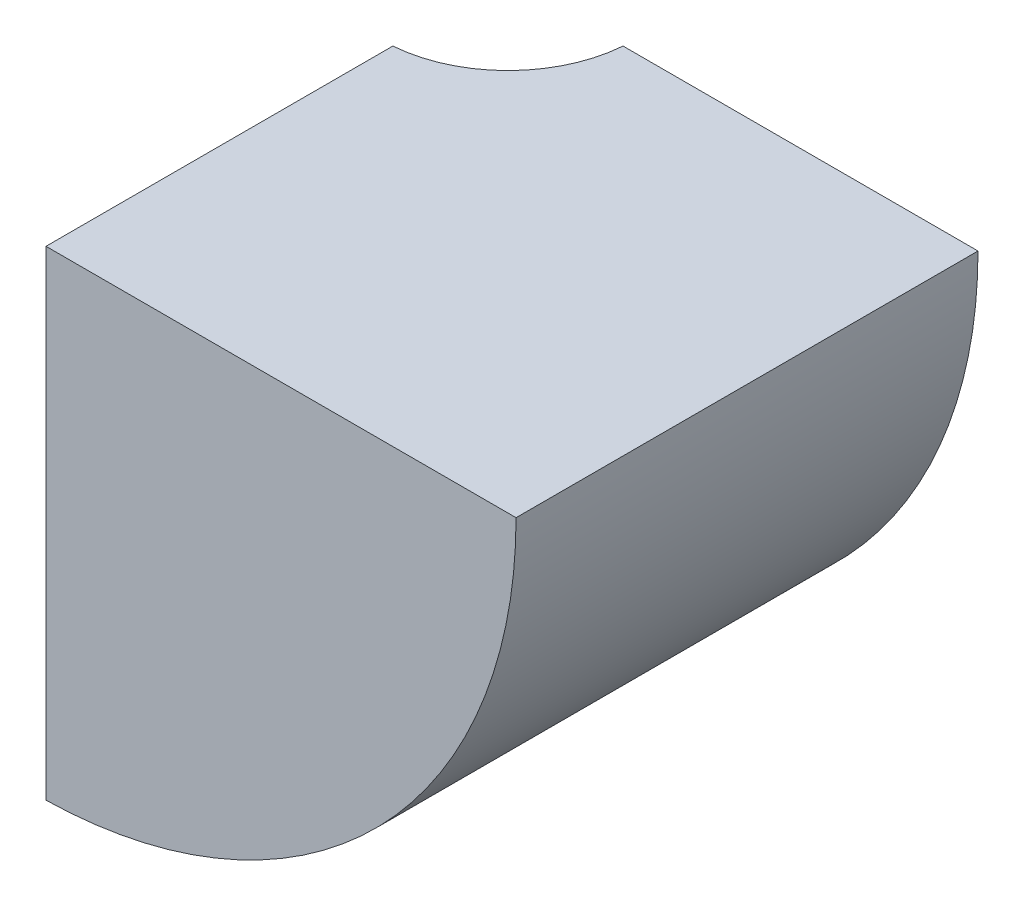
SolidWorks part; units mm, degrees
ref_plane "Front Plane" through (0, 0, 0) normal (0, 0, 1) x (1, 0, 0)
ref_plane "Top Plane" through (0, 0, 0) normal (0, 1, 0) x (1, 0, 0)
ref_plane "Right Plane" through (0, 0, 0) normal (1, 0, 0) x (0, 0, -1)
sketch "Sketch1" plane through (0, 0, 0) normal (0, 0, 1) x (1, 0, 0)
  circle A0 centre (0, 0) radius 29.5
  dimension "D1" = 59
extrude "Boss-Extrude1" add sketch "Sketch1" along normal blind 29
sketch "Sketch2" plane through (0, 0, 29) normal (0, 0, 1) x (1, 0, 0)
  line L0 (0, 0) -> (29.5, 0)
  line L1 (0, 0) -> (0, -29.5)
  circle A0 centre (0, 0) radius 29.5 construction
  arc A1 (29.5, 0) -> (0, -29.5) centre (0, 0) ccw
extrude "Cut-Extrude1" cut sketch "Sketch2" against normal through all
sketch "Sketch3" plane through (0, 0, 0) normal (0, 1, 0) x (1, 0, 0)
  circle A0 centre (0, 0) radius 7.7
  dimension "D1" = 15.4
extrude "Cut-Extrude2" cut sketch "Sketch3" against normal through all
sketch "Sketch4" plane through (0, 0, 0) normal (0, 1, 0) x (1, 0, 0)
  line L1 (0, -29) -> (0.6, -29)
  line L2 (0, -29) -> (0, -6.788)
  line L3 (0, -6.788) -> (0.6, -6.788)
  line L4 (0.6, -29) -> (0.6, -6.788)
  line L5 (29.5, 0) -> (6.2585, 0)
  line L6 (29.5, 0) -> (29.5, -0.6)
  line L7 (29.5, -0.6) -> (6.2585, -0.6)
  line L8 (6.2585, 0) -> (6.2585, -0.6)
  dimension "D1" = 0.6
  dimension "D2" = 0.6
extrude "Cut-Extrude3" cut sketch "Sketch4" against normal through all
